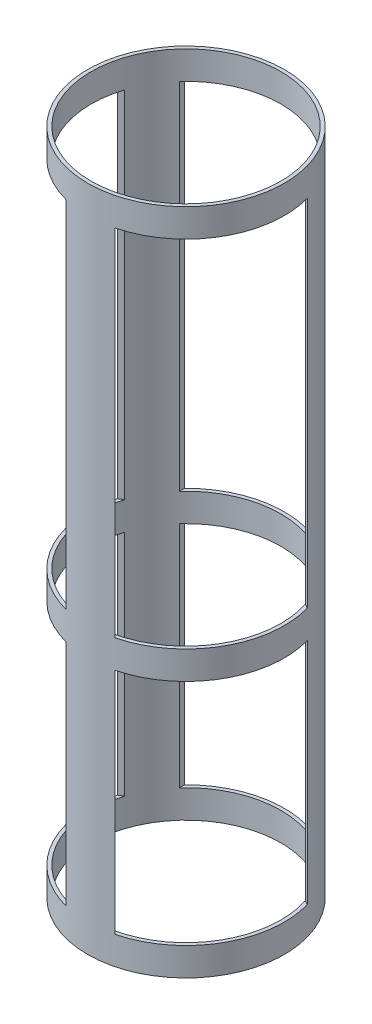
SolidWorks part; units mm, degrees
material "6061-T6 (SS)"
ref_plane "Front Plane" through (0, 0, 0) normal (0, 0, 1) x (1, 0, 0)
ref_plane "Top Plane" through (0, 0, 0) normal (0, 1, 0) x (1, 0, 0)
ref_plane "Right Plane" through (0, 0, 0) normal (1, 0, 0) x (0, 0, -1)
sketch "Sketch1" plane through (0, 0, 0) normal (0, 1, 0) x (1, 0, 0)
  circle A0 centre (0, 0) radius 88.9
  circle A1 centre (0, 0) radius 85.725
  dimension "D1" = 177.8
  dimension "D2" = 171.45
extrude "Boss-Extrude1" add sketch "Sketch1" along normal mid plane 603.25
sketch "Sketch2" plane through (0, 0, 0) normal (0, 0, 1) x (1, 0, 0)
  line L0 (88.9, -301.625) -> (88.9, 301.625) construction
  line L5 (-88.9, -301.625) -> (88.9, -301.625) construction
  line L6 (63.5, -276.225) -> (-63.5, -276.225)
  line L7 (-88.9, 301.625) -> (-88.9, -301.625) construction
  line L9 (63.5, -276.225) -> (63.5, -69.723)
  line L10 (63.5, -69.723) -> (-63.5, -69.723)
  line L11 (-63.5, -276.225) -> (-63.5, -69.723)
  line L12 (85.725, 301.625) -> (-85.725, 301.625) construction
  line L13 (63.5, -44.323) -> (-63.5, -44.323)
  line L14 (63.5, -44.323) -> (63.5, 276.225)
  line L15 (63.5, 276.225) -> (-63.5, 276.225)
  line L16 (-63.5, -44.323) -> (-63.5, 276.225)
  dimension "D1" = 25.4
  dimension "D2" = 25.4
  dimension "D3" = 25.4
  dimension "D4" = 231.902
  dimension "D5" = 25.4
  dimension "D6" = 25.4
extrude "Cut-Extrude1" cut sketch "Sketch2" against normal up to surface (62.217 mm away)
pattern_circular "CirPattern1" count 3 over 360 about axis through (0, 0, 0) along (0, 1, 0) of "Cut-Extrude1"
ref_plane "Plane1" through (0, 0, 88.9) normal (0, 0, 1) x (1, 0, 0)
sketch "Sketch3" plane through (0, 0, 88.9) normal (0, 0, 1) x (1, 0, 0)
  line L0 (0, -97.79) -> (0, 97.79) construction
  line L1 (88.9, 301.625) -> (-88.9, 301.625) construction
  circle A0 centre (0, 295.275) radius 1.4351
  dimension "D1" = 2.8702
  dimension "D2" = 6.35
extrude "Cut-Extrude2" [suppressed] cut sketch "Sketch3" against normal blind 25.908
pattern_circular "CirPattern2" [suppressed] count 12 over 360
mirror "Mirror1" [suppressed] about plane through (0, 0, 0) normal (0, 1, 0)
sketch "Sketch4" [suppressed] plane through (0, 0, 88.9) normal (0, 0, 1) x (1, 0, 0)
  line L0 (0, -97.79) -> (0, 97.79) construction
  circle A0 centre (0, -225.425) radius 1.4351
  circle A1 centre (0, -212.725) radius 1.4351
  circle A2 centre (0, -295.275) radius 1.4351 construction
  circle A3 centre (0, -149.225) radius 1.4351
  circle A4 centre (0, -136.525) radius 1.4351
  dimension "D1" = 69.85
  dimension "D2" = 2.8702
  dimension "D3" = 12.7
  dimension "D4" = 2.8702
  dimension "D5" = 63.5
  dimension "D6" = 12.7
  dimension "D7" = 2.8702
  dimension "D8" = 2.8702
extrude "Cut-Extrude3" [suppressed] cut sketch "Sketch4" against normal blind 34.798
pattern_circular "CirPattern3" [suppressed] count 3 over 360
sketch "Sketch5" [suppressed] plane through (0, 0, 88.9) normal (0, 0, 1) x (1, 0, 0)
  line L0 (0, -97.79) -> (0, 97.79) construction
  line L1 (63.5, -44.323) -> (-63.5, -44.323) construction
  circle A0 centre (0, -57.023) radius 1.4351
  circle A1 centre (0, 60.325) radius 1.4351
  circle A2 centre (0, 177.927) radius 1.4351
  circle A3 centre (0, 295.275) radius 1.4351 construction
  dimension "D1" = 2.8702
  dimension "D3" = 117.348
  dimension "D5" = 2.8702
  dimension "D6" = 2.8702
  dimension "D2" = 12.7
  dimension "D4" = 117.348
extrude "Cut-Extrude4" [suppressed] cut sketch "Sketch5" against normal blind 87.63
pattern_circular "CirPattern4" [suppressed] count 12 over 360
